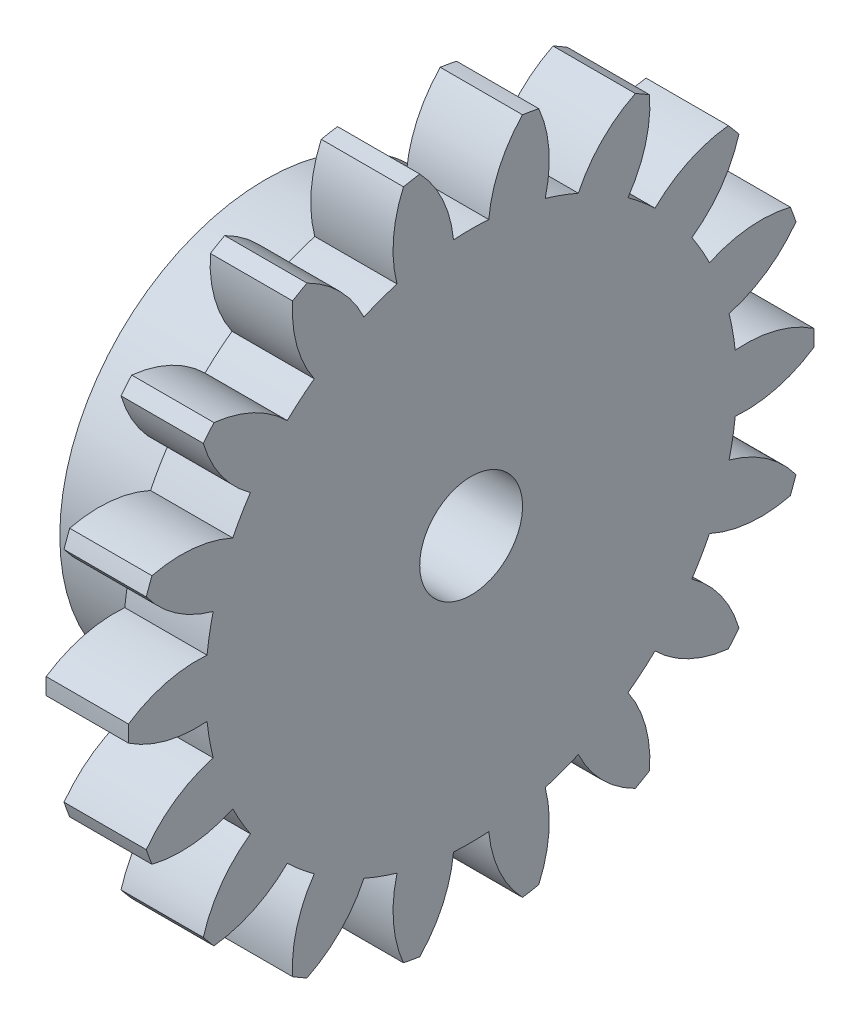
SolidWorks part; units mm, degrees
material "6061-T6 (SS)"
ref_plane "Plane1" through (0, 0, 0) normal (0, 0, 1) x (1, 0, 0)
ref_plane "Plane2" through (0, 0, 0) normal (0, 1, 0) x (1, 0, 0)
ref_plane "Plane3" through (0, 0, 0) normal (1, 0, 0) x (0, 0, -1)
sketch "HoldingSke" plane through (0, 0, 0) normal (0, 1, 0) x (1, 0, 0)
  line L0 (0, 0) -> (289.882, -94.1884)
  line L1 (-15, 0) -> (100, 0) construction
  line L2 (0, 0) -> (-2.1039, 2.3779)
  line L3 (0, 0) -> (-11.863, 4.5341)
  line L4 (0, 0) -> (8.2133, 2.6687)
  line L5 (0, 0) -> (-11.8993, -4.4381)
  line L6 (0, 0) -> (-4.2111, -2.8413)
  line L7 (-2.1039, 2.3779) -> (0.6298, 14.7802)
  line L8 (-76.2, 54.61) -> (-69.596, 54.61)
  line L9 (-71.009, 38.7566) -> (-53.1078, 45.2721)
  line L10 (-76.2, 71.12) -> (104.1128, 71.12)
  line L11 (0, 0) -> (-5.08, 0)
  line L12 (-76.2, 101.6) -> (-76.1147, 101.6)
  line L13 (24.9733, 27.94) -> (52.9518, 28.4284)
  line L14 (24.9733, 27.94) -> (24.9746, 27.94)
  line L15 (24.9733, 27.94) -> (100.4006, 29.5858)
  circle A0 centre (0, 0) radius 3.175
  circle A1 centre (0, 0) radius 12.7
  circle A2 centre (0, 0) radius 12.7
  circle A3 centre (0, 0) radius 3.175
  dimension "MHD" = 25.4
  dimension "Hub_dia" = 25.4
  dimension "Bore" = 6.35
  dimension "MBD" = 6.35
  dimension "Num_teeth" = 18
  dimension "Pitch" = 304.8
  dimension "Overall_len" = 12.7
  dimension "Show_teeth" = 18
  dimension "Thickness" = 5.08
  dimension "OAL" = 12.7001
  dimension "T_dim" = 6.604
  dimension "Ap" = 20
  dimension "H" = 19.05
  dimension "Pitch_radius" = 180.3128
  dimension "Width" = 5.08
  dimension "Backlash" = 0.0853
  dimension "Addendum_fac" = 1
  dimension "Dedendum_fac" = 1.25
  dimension "Clearance_fac" = 0.25
  dimension "Dedendum_add" = 0.0013
sketch "BasProSke" plane through (0, 0, 0) normal (0, 1, 0) x (1, 0, 0)
  line L0 (-10, 0) -> (60, 0) construction
  line L1 (0, 0) -> (0, 21.1667)
  line L2 (0, 0) -> (5.08, 0)
  line L3 (5.08, 0) -> (5.08, 21.1667)
  line L4 (5.08, 21.1667) -> (0, 21.1667)
  dimension "Thickness" = 5.08
  dimension "Diameter" = 42.3333
revolve "Base-Revolve" add sketch "BasProSke" angle 360 about L0
sketch "TooCutSke" plane through (0, 0, 0) normal (1, 0, 0) x (0, 0, -1)
  line L1 (0, 0) -> (0, 107) construction
  line L2 (0, 0) -> (-1.8096, 18.9639) construction
  line L3 (0, 0) -> (-6.5952, 37.403) construction
  line L4 (-1.8096, 18.9639) -> (-3.2976, 18.7015) construction
  arc A0 (1.0883, 16.3668) -> (-1.0883, 16.3668) centre (0, 0) ccw
  arc A1 (3.1925, 20.9502) -> (-3.1925, 20.9502) centre (0, 0) ccw
  circle A2 centre (0, 0) radius 19.05 construction
  circle A3 centre (0, 0) radius 17.9011 construction
  arc A4 (-1.0883, 16.3668) -> (-3.1925, 20.9502) centre (-8.6754, 15.6585) ccw
  arc A5 (3.1925, 20.9502) -> (1.0883, 16.3668) centre (8.6754, 15.6585) ccw
  dimension "Root_dia" = 32.8058
  dimension "Overcut_dia" = 42.3841
  dimension "Pitch_dia" = 38.1
  dimension "Base_dia" = 35.8023
  dimension "Flank_rad" = 7.62
  dimension "Half_ang" = 10
  dimension "Half_CT" = 1.511
extrude "ToothCut" cut sketch "TooCutSke" along normal through all
fillet "Breaks" [suppressed] radius 0.0423
fillet "RootFillets" [suppressed] radius 0.5304
pattern_circular "TeethCuts" count 18 every 20 about axis through (-10, 0, 0) along (1, 0, 0) of "ToothCut", "RootFillets", "Breaks"
sketch "HubNeaOneSke" plane through (0, 0, 0) normal (-1, 0, 0) x (0, 0, 1)
  circle A0 centre (0, 0) radius 12.7
  dimension "Diameter" = 25.4
extrude "HubNearOne" add sketch "HubNeaOneSke" along normal blind 7.6201
sketch "HubNeaBotSke" plane through (0, 0, 0) normal (-1, 0, 0) x (0, 0, 1)
  circle A0 centre (0, 0) radius 12.7
  dimension "Diameter" = 25.4
extrude "HubNearBoth" [suppressed] add sketch "HubNeaBotSke" along normal blind 3.81
ref_plane "FarPln" through (5.08, 0, 0) normal (1, 0, 0) x (0, 0, -1)
sketch "HubFarSke" plane through (5.08, 0, 0) normal (1, 0, 0) x (0, 0, -1)
  circle A0 centre (0, 0) radius 12.7
  dimension "Diameter" = 25.4
extrude "HubFar" [suppressed] add sketch "HubFarSke" along normal blind 3.81
sketch "BorSke" plane through (0, 0, 0) normal (1, 0, 0) x (0, 0, -1)
  circle A0 centre (0, 0) radius 3.175
  dimension "Diameter" = 6.35
extrude "Bore" cut sketch "BorSke" along normal mid plane 25.4001
sketch "KeySke" plane through (0, 0, 0) normal (1, 0, 0) x (0, 0, -1)
  line L0 (-0.127, 0) -> (-0.127, 3.429)
  line L1 (-0.127, 3.429) -> (0.127, 3.429)
  line L2 (0.127, 3.429) -> (0.127, 0)
  line L3 (0, 0) -> (0, 34) construction
  line L4 (-0.127, 0) -> (0.127, 0)
  dimension "Offset" = 3.429
  dimension "Width" = 0.254
extrude "Keyway" [suppressed] cut sketch "KeySke" along normal mid plane 25.4001
pattern_circular "Keyway2" [suppressed] count 2 every 90 about axis through (-10, 0, 0) along (1, 0, 0)
equation "' \"Pitch@HoldingSke\" = 4"
equation "' \"Num_teeth@HoldingSke\" = 12"
equation "' \"Ap@HoldingSke\" =  20"
equation "' \"Ap@HoldingSke\" = 20"
equation "' \"Width@HoldingSke\" = 0.5"
equation "' \"Hub_dia@HoldingSke\"= 1"
equation "' \"Hub_dia@HoldingSke\" = 1"
equation "' \"Overall_len@HoldingSke\" = 1.0"
equation "' \"Bore@HoldingSke\" = 0.75"
equation "' \"T_dim@HoldingSke\" = 0.85"
equation "' \"Width@KeySke\" = 0.25"
equation "' \"Show_teeth@HoldingSke\" = 13"
equation "' \"Backlash@HoldingSke\" = 0.009"
equation "' \"Addendum_fac@HoldingSke\" = 1.0"
equation "' \"Dedendum_fac@HoldingSke\" = 1.25"
equation "' \"Dedendum_add@HoldingSke\" = 0.00005"
equation "' \"Clearance_fac@HoldingSke\" = 0.25"
equation "' \"Pitch@HoldingSke\" = 0.5"
equation "' \"Num_teeth@HoldingSke\" = 23"
equation "' \"Show_teeth@HoldingSke\" = 23"
equation "' \"Backlash@HoldingSke\" = 0.0375"
equation "\"Overcut_dia@TooCutSke\" = (\"Num_teeth@HoldingSke\" + 2 * \"Addendum_fac@HoldingSke\") / \"Pitch@HoldingSke\" + 0.002"
equation "\"Pitch_dia@TooCutSke\" = \"Num_teeth@HoldingSke\" / \"Pitch@HoldingSke\""
equation "\"Base_dia@TooCutSke\" = \"Num_teeth@HoldingSke\" / \"Pitch@HoldingSke\" * cos((\"Ap@HoldingSke\"  * 3.14159265 / 180))"
equation "\"Root_dia@TooCutSke\" = (\"Num_teeth@HoldingSke\" + 2) / \"Pitch@HoldingSke\" - 2 * (\"Addendum_fac@HoldingSke\" + \"Dedendum_fac@HoldingSke\") / \"Pitch@HoldingSke\" - \"Dedendum_add@HoldingSke\" * 2"
equation "\"Half_ang@TooCutSke\" = 180 / \"Num_teeth@HoldingSke\""
equation "\"Half_CT@TooCutSke\" = \"Num_teeth@HoldingSke\" / \"Pitch@HoldingSke\" * sin((3.14159265 / 2 / \"Num_teeth@HoldingSke\")) / 2 - 7 * \"Backlash@HoldingSke\" / 4"
equation "\"Flank_rad@TooCutSke\" = \"Num_teeth@HoldingSke\" / \"Pitch@HoldingSke\" / 5"
equation "\"Radius@RootFillets\" = \"Clearance_fac@HoldingSke\" / \"Pitch@HoldingSke\" + \"Dedendum_add@HoldingSke\""
equation "\"Break_rad@Breaks\" = 0.02 / \"Pitch@HoldingSke\""
equation "\"Thickness@HoldingSke\" = \"Width@HoldingSke\""
equation "\"OAL@HoldingSke\" = \"Thickness@HoldingSke\""
equation "\"MHD@HoldingSke\" = (\"Num_teeth@HoldingSke\" + 2) / \"Pitch@HoldingSke\" - 2 * (\"Addendum_fac@HoldingSke\" + \"Dedendum_fac@HoldingSke\")  / \"Pitch@HoldingSke\" - \"Dedendum_add@HoldingSke\" * 2"
equation "\"MBD@HoldingSke\" = (\"Num_teeth@HoldingSke\" + 2) / \"Pitch@HoldingSke\" - 2 * (\"Addendum_fac@HoldingSke\" + \"Dedendum_fac@HoldingSke\")  / \"Pitch@HoldingSke\" - \"Dedendum_add@HoldingSke\" * 2 - 0.002"
equation "\"MHD@HoldingSke\" = ((sgn( \"MHD@HoldingSke\" - \"Hub_dia@HoldingSke\" )-1)*( \"MHD@HoldingSke\" - \"Hub_dia@HoldingSke\" ))/-2+ \"Hub_dia@HoldingSke\""
equation "\"MBD@HoldingSke\" = ((sgn( \"MBD@HoldingSke\" - \"Bore@HoldingSke\" )-1)*( \"MBD@HoldingSke\" - \"Bore@HoldingSke\" ))/-2+ \"Bore@HoldingSke\""
equation "\"OAL@HoldingSke\" = ((sgn( \"OAL@HoldingSke\" - \"Overall_len@HoldingSke\" )+1)*( \"OAL@HoldingSke\" - \"Overall_len@HoldingSke\" ))/2 + \"Overall_len@HoldingSke\" + 0.000002"
equation "\"Num_teeth@TeethCuts\" = int( \"Show_teeth@HoldingSke\" ) + 1"
equation "\"Num_teeth@TeethCuts\" = ((sgn( \"Num_teeth@TeethCuts\" - \"Num_teeth@HoldingSke\" )-1)*( \"Num_teeth@TeethCuts\" - \"Num_teeth@HoldingSke\" ))/-2+ \"Num_teeth@HoldingSke\""
equation "\"Num_teeth@TeethCuts\" = ((sgn( \"Num_teeth@TeethCuts\" - 2.0)+1)*( \"Num_teeth@TeethCuts\" - 2.0))/2 +2.0"
equation "\"Angle@TeethCuts\" = 360.0 / \"Num_teeth@HoldingSke\""
equation "\"Diameter@BasProSke\" = (\"Num_teeth@HoldingSke\" + 2 * \"Addendum_fac@HoldingSke\") / \"Pitch@HoldingSke\""
equation "\"Thickness@BasProSke\"  = \"Thickness@HoldingSke\""
equation "' \"Fillet_rad@BasProSke\" =  \"Thickness@HoldingSke\" * 0.05"
equation "' \"Fillet_rad@BasProSke\" = \"Thickness@HoldingSke\" * 0.05"
equation "\"MHD@HoldingSke\" = ((sgn( \"MHD@HoldingSke\" - \"Root_dia@TooCutSke\" )-1)*( \"MHD@HoldingSke\" - \"Root_dia@TooCutSke\" ))/-2+ \"Root_dia@TooCutSke\""
equation "\"Diameter@HubNeaOneSke\" = \"MHD@HoldingSke\""
equation "\"Length@HubNearOne\" = \"OAL@HoldingSke\" - \"Thickness@BasProSke\""
equation "\"Diameter@HubNeaBotSke\" = \"MHD@HoldingSke\""
equation "\"Length@HubNearBoth\" = ( \"OAL@HoldingSke\" - \"Thickness@BasProSke\" ) / 2.0"
equation "\"Thickness@FarPln\" = \"Thickness@BasProSke\""
equation "\"Diameter@HubFarSke\" = \"MHD@HoldingSke\""
equation "\"Length@HubFar\" = ( \"OAL@HoldingSke\" - \"Thickness@BasProSke\" ) / 2.0"
equation "\"Diameter@BorSke\" = \"MBD@HoldingSke\""
equation "\"D1@Bore\" = \"OAL@HoldingSke\" * 2.0"
equation "\"D1@Keyway\" = \"OAL@HoldingSke\" * 2.0"
equation "\"Offset@KeySke\" = \"T_dim@HoldingSke\" - \"MBD@HoldingSke\" / 2.0"
